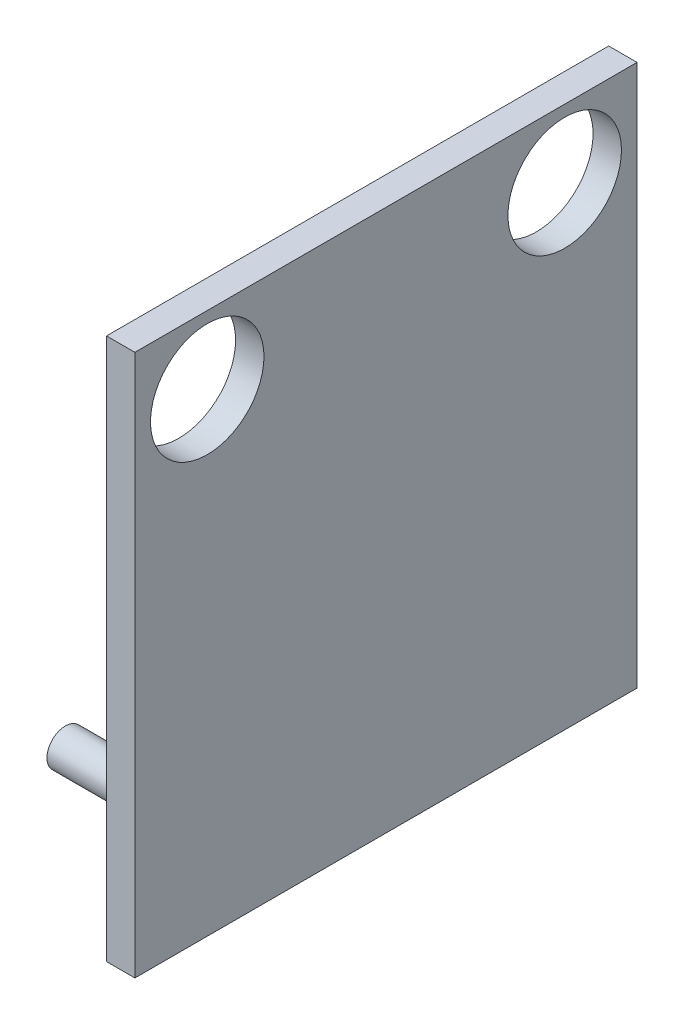
SolidWorks part; units mm, degrees
ref_plane "Front Plane" through (0, 0, 0) normal (0, 0, 1) x (1, 0, 0)
ref_plane "Top Plane" through (0, 0, 0) normal (0, 1, 0) x (1, 0, 0)
ref_plane "Right Plane" through (0, 0, 0) normal (1, 0, 0) x (0, 0, -1)
sketch "Sketch1" plane through (0, 0, 0) normal (1, 0, 0) x (0, 0, -1)
  line L1 (0, 0) -> (17.7, 0)
  line L2 (0, 0) -> (0, 19.1)
  line L3 (0, 19.1) -> (17.7, 19.1)
  line L4 (17.7, 0) -> (17.7, 19.1)
  circle A0 centre (15.15, 16.7) radius 2
  circle A1 centre (2.55, 16.7) radius 2
  point P9 (8.85, 19.1)
  dimension "D3" = 16.7
  dimension "D4" = 12.6
  dimension "D5" = 6.3
  dimension "D6" = 4
  dimension "D1" = 17.7
  dimension "D2" = 19.1
extrude "Boss-Extrude1" add sketch "Sketch1" along normal blind 1
sketch "Sketch2" plane through (0, 0, 0) normal (-1, 0, 0) x (0, 0, 1)
  line L0 (-17.7, 19.1) -> (0, 19.1) construction
  line L1 (-15.85, 3.54) -> (-1.85, 3.54)
  line L2 (-15.85, 3.54) -> (-15.85, 1)
  line L3 (-15.85, 1) -> (-1.85, 1)
  line L4 (-1.85, 3.54) -> (-1.85, 1)
  line L5 (-11.35, 12.05) -> (-6.35, 12.05)
  line L6 (-11.35, 12.05) -> (-11.35, 7.05)
  line L7 (-11.35, 7.05) -> (-6.35, 7.05)
  line L8 (-6.35, 12.05) -> (-6.35, 7.05)
  line L9 (-17.7, 0) -> (-17.7, 19.1) construction
  line L10 (0, 0) -> (-17.7, 0) construction
  point P10 (-8.85, 19.1)
  point P11 (-8.85, 12.05)
  point P14 (-17.7, 9.55)
  point P15 (-11.35, 9.55)
  point P18 (-8.85, 3.54)
  dimension "D1" = 5
  dimension "D2" = 5
  dimension "D3" = 2.54
  dimension "D4" = 14
  dimension "D5" = 1
extrude "Boss-Extrude2" add sketch "Sketch2" along normal blind 1
sketch "Sketch3" plane through (-1, 0, 0) normal (-1, 0, 0) x (0, 0, 1)
  line L0 (-15.85, 3.54) -> (-15.85, 1) construction
  circle A0 centre (-14.35, 2.27) radius 1.15
  circle A1 centre (-11.65, 2.27) radius 1.15
  circle A2 centre (-8.95, 2.27) radius 1.15
  circle A3 centre (-6.25, 2.27) radius 1.15
  circle A4 centre (-3.55, 2.27) radius 1.15
  point P4 (-15.85, 2.27)
  dimension "D1" = 2.3
  dimension "D2" = 1.5
  dimension "D3" = 5
extrude "Boss-Extrude3" add sketch "Sketch3" along normal blind 1
sketch "Sketch4" plane through (-2, 0, 0) normal (-1, 0, 0) x (0, 0, 1)
  circle A0 centre (-14.35, 2.27) radius 0.65
  circle A1 centre (-11.65, 2.27) radius 0.65
  circle A2 centre (-8.95, 2.27) radius 0.65
  circle A3 centre (-6.25, 2.27) radius 0.65
  circle A4 centre (-3.55, 2.27) radius 0.65
  dimension "D1" = 1.3
  dimension "D2" = 5
extrude "Boss-Extrude4" add sketch "Sketch4" along normal blind 3
